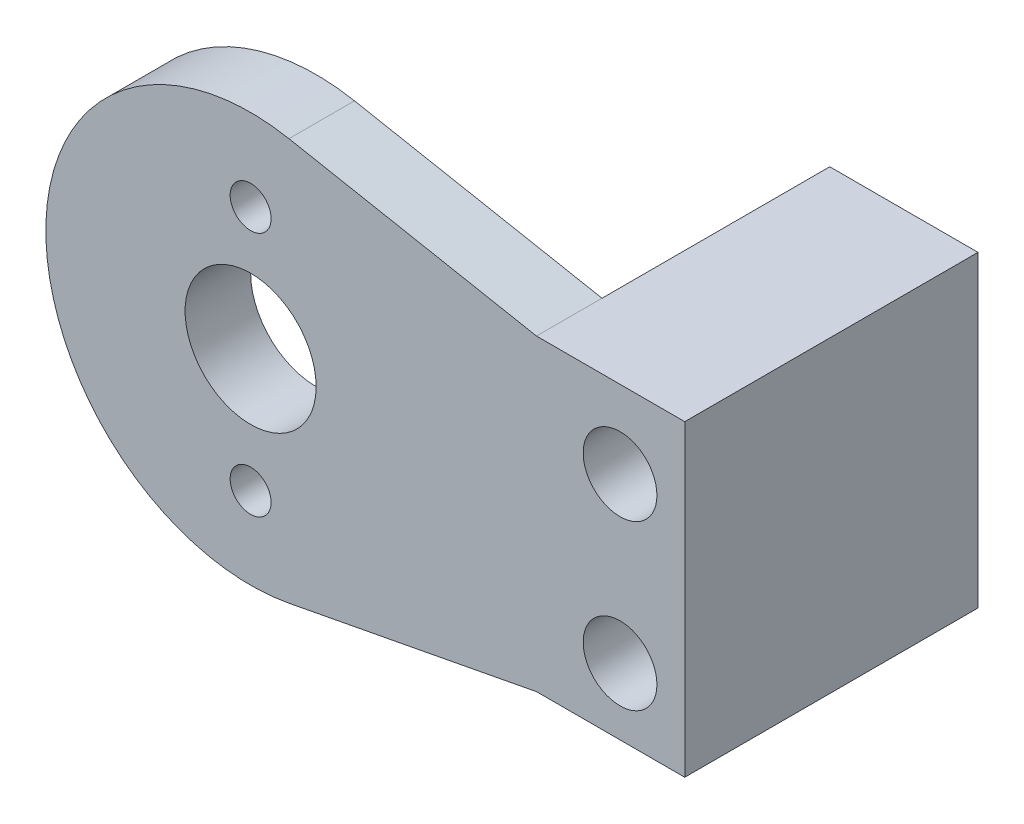
SolidWorks part; units mm, degrees
material "PLA"
ref_plane "Front Plane" through (0, 0, 0) normal (0, 0, 1) x (1, 0, 0)
ref_plane "Top Plane" through (0, 0, 0) normal (0, 1, 0) x (1, 0, 0)
ref_plane "Right Plane" through (0, 0, 0) normal (1, 0, 0) x (0, 0, -1)
ref_plane "Plane1" through (0, 0, 79.9405) normal (0, 0, -1) x (-1, 0, 0)
sketch "Sketch1" plane through (0, 0, 79.9405) normal (0, 0, -1) x (-1, 0, 0)
  line L0 (9.05, 0) -> (24.1604, -2.8791)
  line L1 (9.05, 18.8) -> (24.1604, 21.6791)
  line L25 (9.05, 18.8) -> (0, 18.8)
  line L26 (0, 18.8) -> (0, 0)
  line L27 (0, 0) -> (9.05, 0)
  line L89 (114.6938, 17.2312) -> (114.6938, -10.9376) construction
  line L90 (0, 9.4) -> (-1.8294, 9.4) construction
  arc A0 (24.1604, -2.8791) -> (24.1604, 21.6791) centre (26.5, 9.4) ccw
  dimension "D7" = 25
  dimension "D1" = 18.8
  dimension "D3" = 9.05
  dimension "D4" = 9.05
  dimension "D5" = 9.4
  dimension "D6" = 0
  dimension "D8" = 26.5
extrude "Boss-Extrude1" add sketch "Sketch1" against normal blind 4
sketch "Sketch2" plane through (0, 0, 79.9405) normal (0, 0, -1) x (-1, 0, 0)
  line L0 (9.05, 0) -> (0, 0)
  line L1 (0, 0) -> (0, 18.8)
  line L2 (0, 18.8) -> (9.05, 18.8)
  line L3 (9.05, 18.8) -> (9.05, 0)
  dimension "D1" = 9.05
  dimension "D2" = 18.8
extrude "Boss-Extrude2" add sketch "Sketch2" along normal blind 13.9
sketch "Sketch3" plane through (0, 0, 83.9405) normal (0, 0, 1) x (1, 0, 0)
  line L0 (-9.05, 18.8) -> (0, 18.8) construction
  line L1 (0, 18.8) -> (0, 0) construction
  line L2 (0, 0) -> (-9.05, 0) construction
  circle A0 centre (-26.5, 9.4) radius 4
  circle A1 centre (-3.95, 14.05) radius 2.25
  circle A2 centre (-3.95, 4.05) radius 2.25
  circle A3 centre (-26.5, 16.9) radius 1.25
  circle A4 centre (-26.5, 1.9) radius 1.25
  arc A5 (-24.1604, 21.6791) -> (-24.1604, -2.8791) centre (-26.5, 9.4) ccw construction
  dimension "D4" = 4.5
  dimension "D5" = 4.5
  dimension "D6" = 8
  dimension "D7" = 2.5
  dimension "D8" = 2.5
  dimension "D2" = 3.95
  dimension "D3" = 10
  dimension "D9" = 1.9
  dimension "D10" = 1.9
  dimension "D11" = 4.75
extrude "Cut-Extrude1" cut sketch "Sketch3" against normal blind 30
